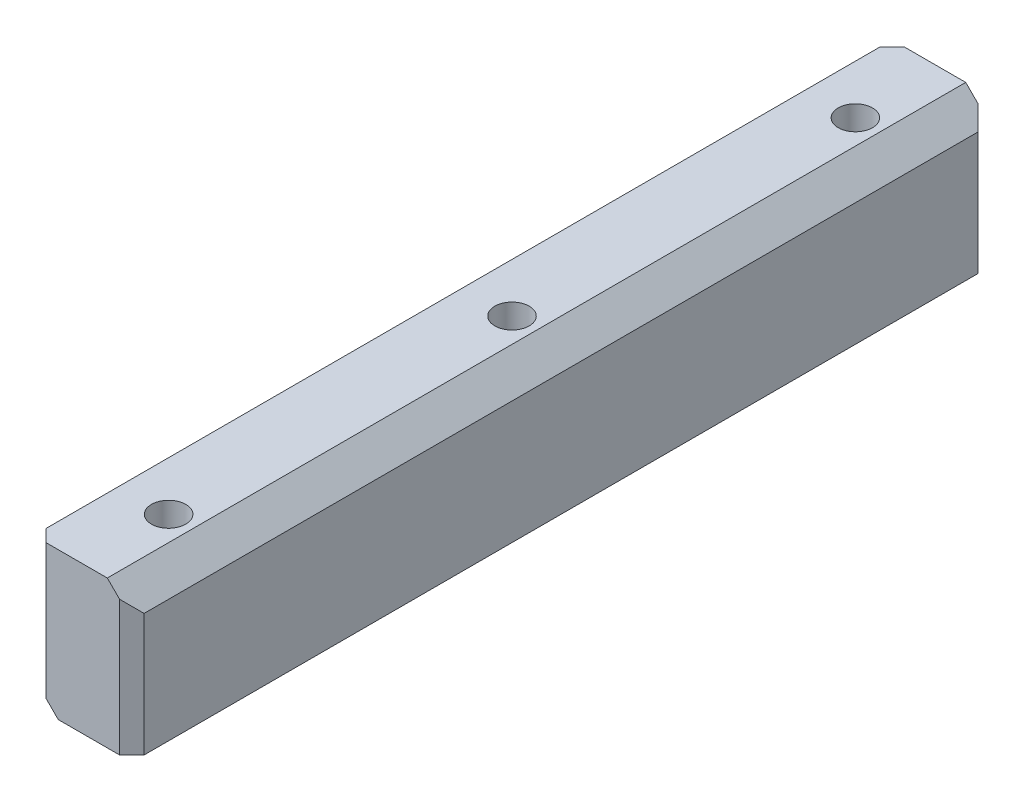
SolidWorks part; units mm, degrees
material "尼龙 101"
ref_plane "前视基准面" through (0, 0, 0) normal (0, 0, 1) x (1, 0, 0)
ref_plane "上视基准面" through (0, 0, 0) normal (0, 1, 0) x (1, 0, 0)
ref_plane "右视基准面" through (0, 0, 0) normal (1, 0, 0) x (0, 0, -1)
sketch "草图1" plane through (0, 0, 0) normal (0, 0, 1) x (1, 0, 0)
  line L1 (0, 0) -> (40, 0)
  line L2 (0, 0) -> (0, -60)
  line L3 (0, -60) -> (40, -60)
  line L4 (40, 0) -> (40, -60)
  dimension "D1" = 40
  dimension "D2" = 60
extrude "凸台-拉伸1" add sketch "草图1" along normal blind 350
chamfer "倒角1" distance 10 2 edges at (0, -60, 175) (40, 0, 175)
hole_wizard "M16 螺纹孔1" positions "草图3" profile "草图4" tap size "M16" standard "GB" end condition through all
sketch "草图3" plane through (0, 0, 0) normal (0, 1, 0) x (1, 0, 0)
  line L0 (0, -350) -> (0, 0) construction
  line L1 (30, -350) -> (0, -350) construction
  line L2 (40, 0) -> (40, -350) construction
  line L3 (0, -345.5807) -> (40, -345.5807) construction
  point P0 (20, -315)
  point P2 (20, -175)
  point P11 (20, -35)
  dimension "D1" = 20
  dimension "D2" = 140
  dimension "D3" = 35
  dimension "D4" = 140
cosmetic thread "孔螺蚊线1"
cosmetic thread "孔螺蚊线2"
cosmetic thread "孔螺蚊线3"
sketch "草图4" plane through (20, 0, 315) normal (1, 0, 0) x (0, 0, 1)
  line L0 (0, 0) -> (0, 60)
  line L1 (0, 60) -> (7, 60)
  line L2 (7, 60) -> (7, 0)
  line L5 (7, 0) -> (0, 0)
  line L11 (0, -6.35) -> (0, 107.95) construction
  dimension "通孔螺纹孔钻头直径" = 14
  dimension "通孔螺纹孔钻头深度" = 60
chamfer "倒角2" distance 5 angle 45 4 edges at (40, -35, 350) (0, -25, 350) (40, -35, 0) (0, -25, 0)
